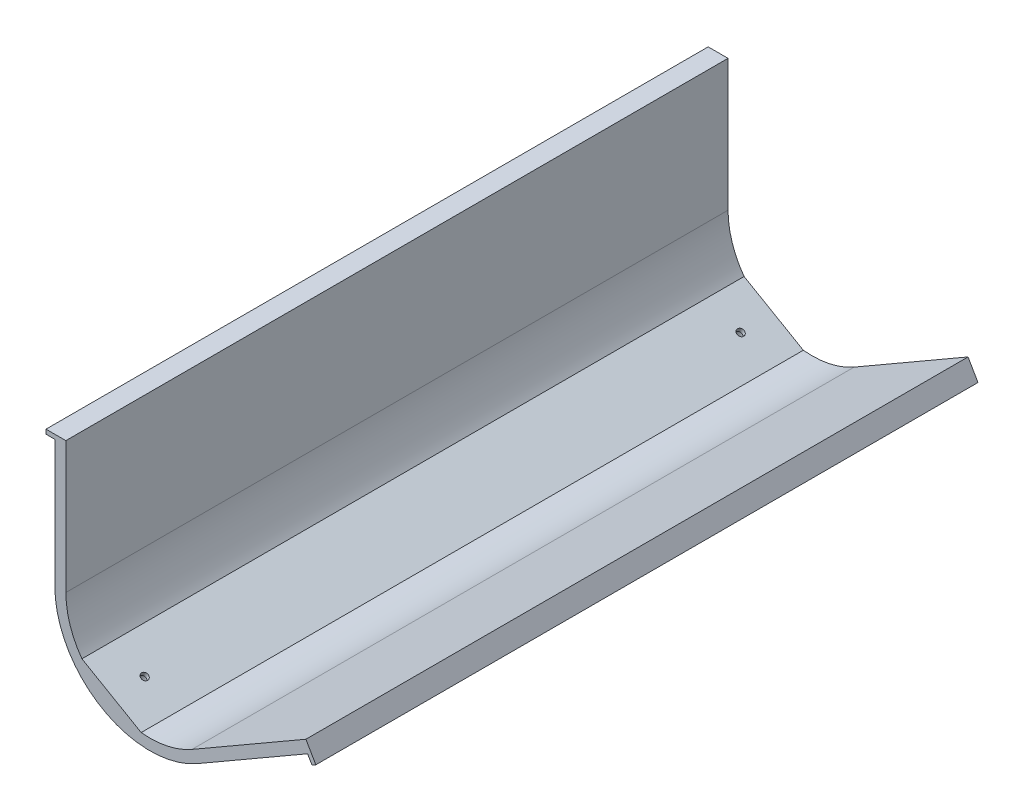
SolidWorks part; units mm, degrees
ref_plane "Front Plane" through (0, 0, 0) normal (0, 0, 1) x (1, 0, 0)
ref_plane "Top Plane" through (0, 0, 0) normal (0, 1, 0) x (1, 0, 0)
ref_plane "Right Plane" through (0, 0, 0) normal (1, 0, 0) x (0, 0, -1)
sketch "Sketch1" plane through (0, 0, 0) normal (0, 0, 1) x (1, 0, 0)
  line L0 (-10, 0) -> (-10, 46.9949) construction
  line L1 (-10, 420) -> (-10, 0) construction
  line L2 (-10.5, 54.093) -> (-10.5, 57.093) construction
  line L3 (-10.5, 57.093) -> (-14.5, 57.093) construction
  line L4 (-14.5, 57.093) -> (-14.5, 60.093) construction
  line L5 (-14.5, 60.093) -> (-4.5, 60.093) construction
  line L6 (-4.5, 60.093) -> (-4.5, 63.093) construction
  line L7 (95.3398, -13.8231) -> (54.641, -37.3205) construction
  line L8 (54.641, -37.3205) -> (418.3717, 172.6795) construction
  line L9 (-10, 0) -> (-10, 46.9949)
  line L10 (-10, 420) -> (-10, 0)
  line L11 (-10.5, 54.093) -> (-10.5, 57.093)
  line L12 (-10.5, 57.093) -> (-14.5, 57.093)
  line L13 (-14.5, 57.093) -> (-14.5, 60.093)
  line L14 (-14.5, 60.093) -> (-4.5, 60.093)
  line L15 (-4.5, 60.093) -> (-4.5, 63.093)
  line L16 (95.3398, -13.8231) -> (54.641, -37.3205)
  line L17 (54.641, -37.3205) -> (418.3717, 172.6795)
  line L18 (7.4103, -25.3516) -> (13.3139, -28.7601) construction
  line L19 (7.4103, -25.3516) -> (13.3139, -28.7601)
  arc A0 (-10, 0) -> (54.641, -37.3205) centre (33.094, 0) ccw construction
  arc A1 (-10, 0) -> (54.641, -37.3205) centre (33.094, 0) ccw
sketch "Sketch2" plane through (0, 0, 0) normal (0, 0, 1) x (1, 0, 0)
  line L0 (-10, 0) -> (-10, 46.9949) construction
  line L1 (-10, 0) -> (-10, 57.593)
  line L2 (-10, 420) -> (-10, 0) construction
  line L6 (-5, 0) -> (-5, 59.593)
  line L7 (-5, 0) -> (-5, 57.593) construction
  line L8 (-10, 59.593) -> (-5, 59.593)
  line L9 (-14, 59.593) -> (-4.5, 59.593)
  line L10 (-14, 57.593) -> (-14, 59.593)
  line L11 (-10.5, 57.593) -> (-14, 57.593)
  line L12 (-14, 59.593) -> (-10, 59.593)
  line L13 (-14, 57.593) -> (-14, 59.593)
  line L14 (-10, 57.593) -> (-14, 57.593)
  line L15 (11.547, -37.3205) -> (14.8632, -31.5767) construction
  line L16 (54.641, -37.3205) -> (104.518, -8.524)
  line L17 (104.518, -8.524) -> (106.518, -11.9881)
  line L18 (106.518, -11.9881) -> (108.2501, -10.9881)
  line L19 (108.2501, -10.9881) -> (106.2501, -7.524)
  line L20 (106.2501, -7.524) -> (103.7501, -3.1939)
  line L21 (52.141, -32.9904) -> (103.7501, -3.1939)
  line L22 (7.4103, -25.3516) -> (13.3139, -28.7601) construction
  line L23 (2.2701, -22.3839) -> (29.1209, -37.8863)
  arc A0 (-10, 0) -> (54.641, -37.3205) centre (33.094, 0) ccw construction
  arc A1 (-10, 0) -> (54.641, -37.3205) centre (33.094, 0) ccw
  arc A2 (-5, 0) -> (2.2701, -22.3839) centre (33.094, 0) ccw
  arc A3 (-5, 0) -> (52.141, -32.9904) centre (33.094, 0) ccw construction
  arc A4 (-10, 0) -> (54.641, -37.3205) centre (33.094, 0) ccw construction
  arc A5 (29.1209, -37.8863) -> (52.141, -32.9904) centre (33.094, 0) ccw
  dimension "D1" = 0.5
  dimension "D2" = 5
extrude "Boss-Extrude1" add sketch "Sketch2" along normal up to surface (300 mm away)
sketch "Sketch3" plane through (-9.125, -15.805, 0) normal (0.5, 0.866, 0) x (0.866, -0.5, 0)
  line L0 (28.6603, 0) -> (28.6603, -300) construction
  line L1 (44.1626, 0) -> (13.1579, 0) construction
  line L2 (44.1626, -300) -> (13.1579, -300) construction
  line L3 (28.6603, -150) -> (18.3372, -150) construction
  circle A0 centre (28.6603, -15) radius 1.6
  circle A1 centre (28.6603, -285) radius 1.6
  dimension "D1" = 3.2
  dimension "D2" = 15
extrude "Cut-Extrude1" cut sketch "Sketch3" against normal through all
sketch "Sketch4" plane through (-9.125, -15.805, 0) normal (0.5, 0.866, 0) x (0.866, -0.5, 0)
  circle A0 centre (28.6603, -15) radius 2.875
  circle A1 centre (28.6603, -285) radius 2.875
  dimension "D1" = 5.75
extrude "Cut-Extrude2" cut sketch "Sketch4" against normal through all from offset 2
equation "\"m3screwdiameter\"=3.2"
equation "\"D1@Sketch3\"=\"m3screwdiameter\""
equation "\"M3Capheaddiameter\"=5.75"
equation "\"D1@Sketch4\"=\"M3Capheaddiameter\""
